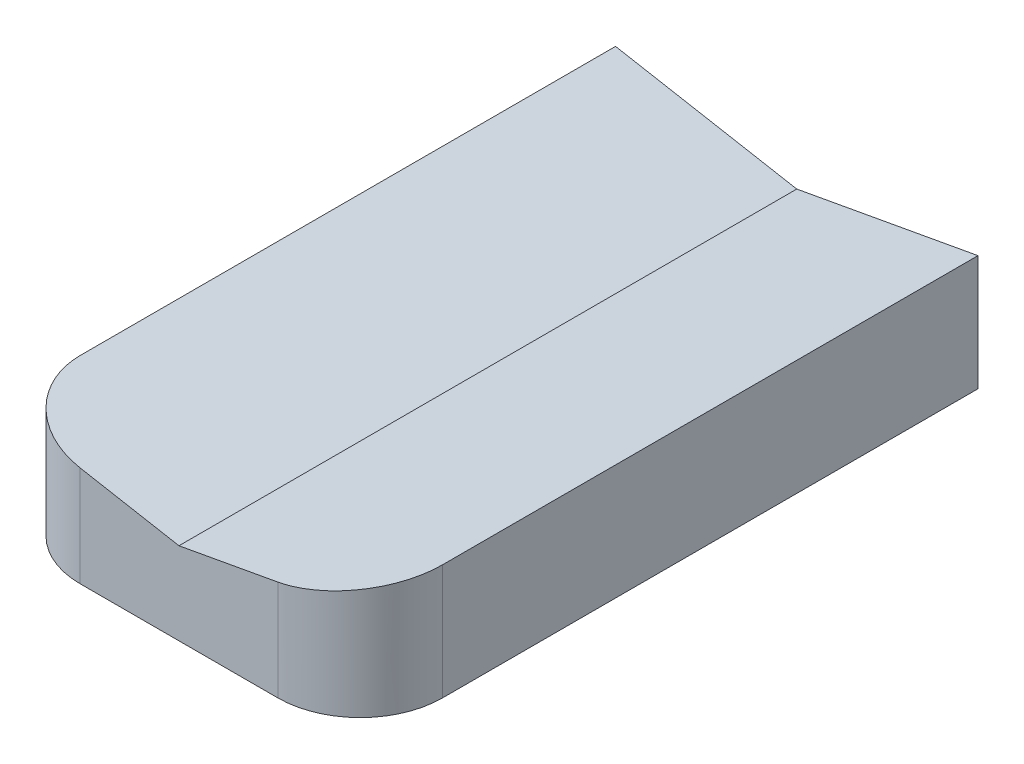
SolidWorks part; units mm, degrees
ref_plane "前视基准面" through (0, 0, 0) normal (0, 0, 1) x (1, 0, 0)
ref_plane "上视基准面" through (0, 0, 0) normal (0, 1, 0) x (1, 0, 0)
ref_plane "右视基准面" through (0, 0, 0) normal (1, 0, 0) x (0, 0, -1)
sketch "草图1" plane through (0, 0, 0) normal (0, -1, 0) x (1, 0, 0)
  line L2 (0, 0) -> (0, -41.1281) construction
  line L5 (-20.8516, 0) -> (21.5299, 0) construction
  line L6 (6, 37.5) -> (-6, 37.5)
  line L7 (-11, 32.5) -> (-11, 0)
  line L8 (-11, 0) -> (11, 0)
  line L9 (11, 0) -> (11, 32.5)
  arc A2 (11, 32.5) -> (6, 37.5) centre (6, 32.5) ccw
  arc A3 (-11, 32.5) -> (-6, 37.5) centre (-6, 32.5) cw
  point P15 (11, 0)
  point P20 (-11, 0)
  dimension "D3" = 5
  dimension "D1" = 11
  dimension "D2" = 32.5
  dimension "D4" = 12
extrude "凸台-拉伸2" add sketch "草图1" along normal blind 7
sketch "草图2" plane through (0, 0, 0) normal (0, 0, -1) x (-1, 0, 0)
  line L0 (0, 0) -> (0, -7.9149) construction
  line L1 (-11, 0) -> (11, 0)
  line L2 (11, 0) -> (0, -2)
  line L3 (0, -2) -> (-11, 0)
  dimension "D1" = 2
extrude "切除-拉伸1" cut sketch "草图2" against normal through all
